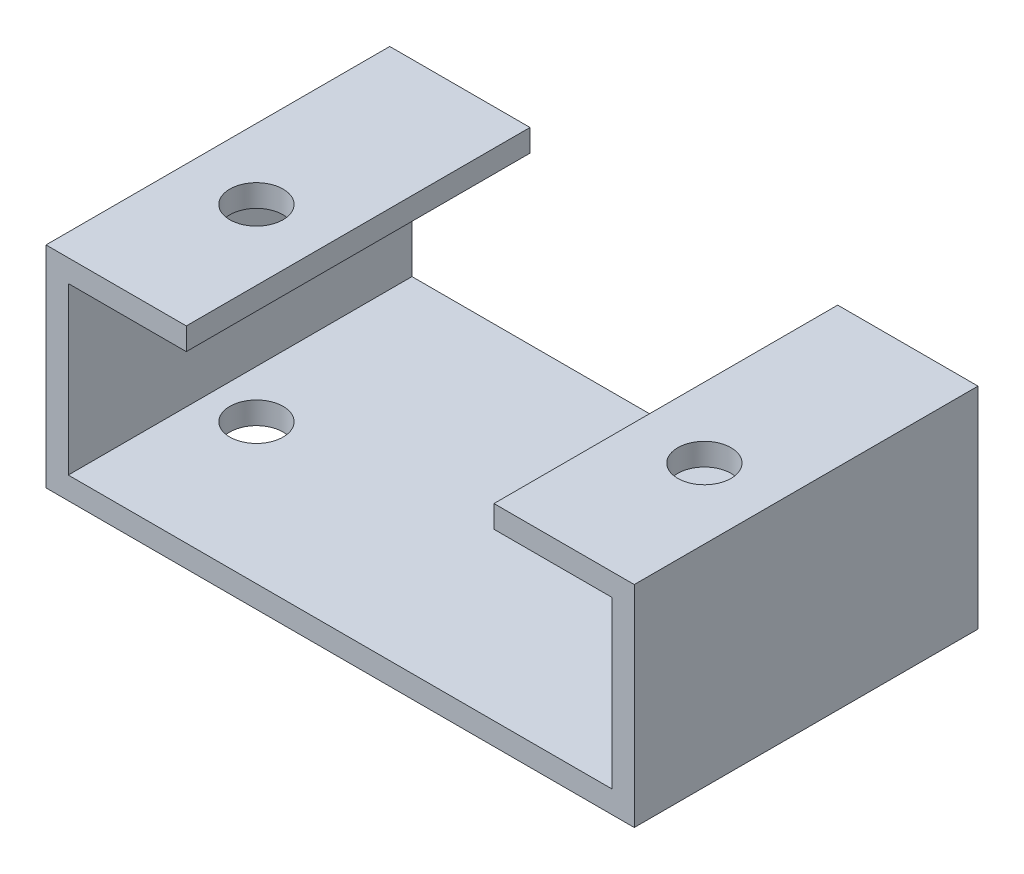
SolidWorks part; units mm, degrees
ref_plane "Front Plane" through (0, 0, 0) normal (0, 0, 1) x (1, 0, 0)
ref_plane "Top Plane" through (0, 0, 0) normal (0, 1, 0) x (1, 0, 0)
ref_plane "Right Plane" through (0, 0, 0) normal (1, 0, 0) x (0, 0, -1)
sketch "Sketch1" plane through (0, 0, 0) normal (0, 0, 1) x (1, 0, 0)
  line L0 (20.965, 0) -> (0, 0)
  line L1 (0, 0) -> (0, 15)
  line L2 (0, 15) -> (10, 15)
  line L3 (20.965, 1.5875) -> (1.5875, 1.5875)
  line L4 (1.5875, 1.5875) -> (1.5875, 13.4125)
  line L5 (1.5875, 13.4125) -> (10, 13.4125)
  line L6 (10, 15) -> (10, 13.4125)
  line L7 (20.965, 1.5875) -> (20.965, 0)
  dimension "D1" = 15
  dimension "D2" = 20.965
  dimension "D3" = 10
  dimension "D4" = 1.5875
extrude "Boss-Extrude1" add sketch "Sketch1" along normal blind 10 and the other way blind 14.5
hole_wizard "#6 Clearance Hole1" positions "Sketch3" profile "Sketch2" hole size "#6" standard "ANSI Inch" end condition through all
sketch "Sketch3" plane through (0, 0, 0) normal (0, -1, 0) x (-1, 0, 0)
  line L4 (0, 0) -> (-20.965, 0) construction
  line L5 (-20.965, 14.5) -> (-20.965, -10) construction
  line L8 (0, 14.5) -> (0, -10) construction
  point P0 (-5, 0)
  dimension "D1" = 5
sketch "Sketch2" plane through (5, 0, 0) normal (1, 0, 0) x (0, 0, -1)
  line L0 (0, 0) -> (0, 15)
  line L1 (0, 15) -> (1.8986, 15)
  line L2 (1.8986, 15) -> (1.8986, 0)
  line L5 (1.8986, 0) -> (0, 0)
  line L11 (0, -6.35) -> (0, 107.95) construction
  dimension "Thru Hole Dia." = 3.7973
  dimension "Thru Hole Depth" = 15
mirror "Mirror1" about plane through (20.965, 1.5875, -14.5) normal (1, 0, 0) of "#6 Clearance Hole1", "Boss-Extrude1"
